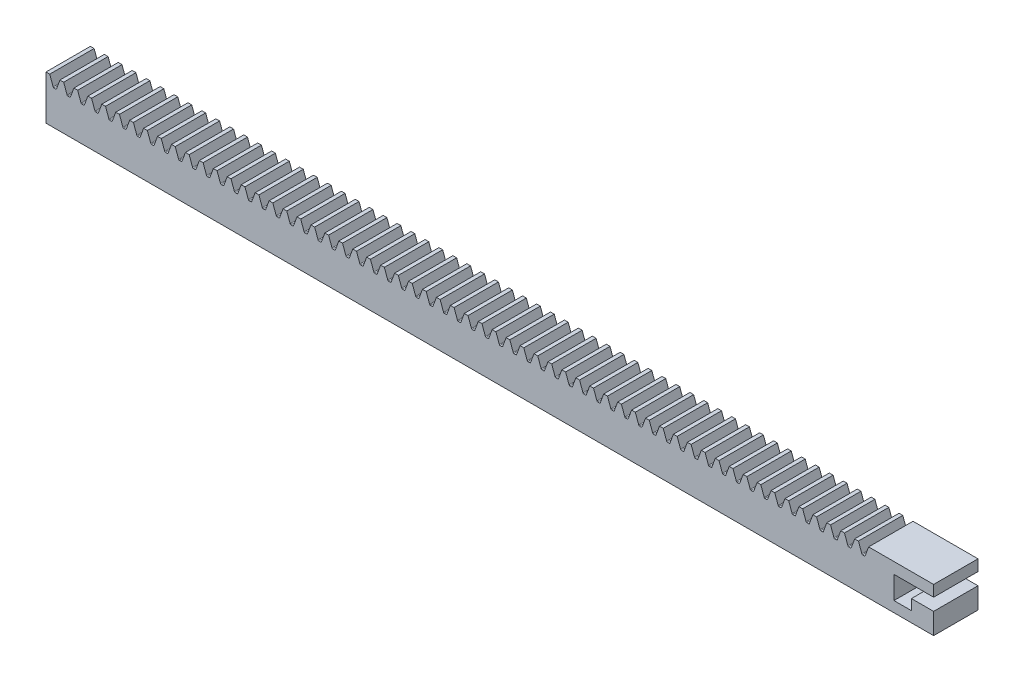
SolidWorks part; units mm, degrees
ref_plane "Front" through (0, 0, 0) normal (0, 0, 1) x (1, 0, 0)
ref_plane "Top" through (0, 0, 0) normal (0, 1, 0) x (1, 0, 0)
ref_plane "Right" through (0, 0, 0) normal (1, 0, 0) x (0, 0, -1)
sketch "Sketch1" plane through (0, 0, 0) normal (0, 0, 1) x (1, 0, 0)
  line L0 (-127, 0) -> (381, 0) construction
  line L1 (-127, -6.35) -> (127, -6.35)
  line L2 (-127, -6.35) -> (-127, 6.35)
  line L3 (-127, 6.35) -> (127, 6.35)
  line L4 (127, -6.35) -> (127, 6.35)
  line L5 (-127, -6.35) -> (127, 6.35) construction
  line L6 (-127, 6.35) -> (127, -6.35) construction
  point P0 (0, 0)
extrude "Boss-Extrude1" add sketch "Sketch1" along normal mid plane 12.7
sketch "Sketch2" plane through (0, 0, 6.35) normal (0, 0, 1) x (1, 0, 0)
  line L0 (-125.9296, 6.35) -> (-124.8941, 3.5052)
  line L1 (127, 6.35) -> (-127, 6.35) construction
  line L2 (-124.8941, 3.5052) -> (-124.0456, 3.5052)
  line L3 (-124.0456, 3.5052) -> (-123.0102, 6.35)
  line L4 (-125.9296, 6.35) -> (-123.0102, 6.35)
  line L5 (-125.4673, 5.08) -> (-121.4775, 5.08) construction
  line L6 (-123.0102, 6.35) -> (-121.9397, 6.35) construction
  line L7 (-123.4724, 3.5052) -> (-123.4724, 6.35) construction
  line L8 (-124.4699, 6.35) -> (-124.4699, 3.5052) construction
  line L10 (-121.9397, 6.35) -> (-120.9043, 3.5052) construction
  line L11 (-121.4775, 6.35) -> (-121.4775, 3.5052) construction
  line L12 (-125.9296, 6.35) -> (-127, 6.35) construction
  point P7 (-123.4724, 5.08)
  point P14 (-125.4673, 5.08)
  dimension "D1" = 1.27
  dimension "D3" = 3.9898
  dimension "D4" = 2.8448
  dimension "D6" = 1.9949
  dimension "D2" = 20
  dimension "D7" = 20
  dimension "D5" = 1.0704
  dimension "D9" = 0.8486
extrude "Cut-Extrude1" cut sketch "Sketch2" against normal blind 12.7
fillet "Fillet3" radius 0.2546 2 edges at (-124.0456, 3.5052, 0) (-124.8941, 3.5052, 0)
pattern_linear "LPattern4" count 59 spacing 3.9898 along (1, 0, 0) of "Cut-Extrude1", "Fillet3"
sketch "Ref" plane through (0, 0, 6.35) normal (0, 0, 1) x (1, 0, 0)
  line L0 (-127, 5.08) -> (127, 5.08) construction
  line L1 (-127, -6.35) -> (-127, 6.35) construction
  line L2 (127, -6.35) -> (127, 6.35) construction
  line L3 (-125.4673, 5.08) -> (-121.4775, 5.08) construction
sketch "Sketch3" plane through (0, 0, 6.35) normal (0, 0, 1) x (1, 0, 0)
  line L1 (127, 6.35) -> (108.4001, 6.35) construction
  line L9 (127, 3.175) -> (115.65, 3.175)
  line L10 (127, -6.35) -> (127, 6.35) construction
  line L11 (115.65, 3.175) -> (115.65, -3.325)
  line L12 (115.65, -3.325) -> (120.65, -3.325)
  line L13 (120.65, -3.325) -> (120.65, -0.325)
  line L14 (120.65, -0.325) -> (127, -0.325)
  line L15 (127, 3.175) -> (127, -0.325)
  dimension "D1" = 5
  dimension "D2" = 3
  dimension "D3" = 3.5
  dimension "D4" = 3.175
  dimension "D5" = 6.35
extrude "Cut-Extrude2" cut sketch "Sketch3" against normal through all
equation "\"D1@Sketch2\" = 1/\"Diamteral Pitch@Sketch1\""
equation "\"D3@Sketch2\" = 3.1416/\"Diamteral Pitch@Sketch1\""
equation "\"D4@Sketch2\" = (2.2/\"Diamteral Pitch@Sketch1\")+.002"
equation "\"D3@LPattern4\" =\"D3@Sketch2\""
equation "\"D1@Fillet3\" = \"D9@Sketch2\"*.3"
equation "\"D1@Cut-Extrude1\" = \"D1@Boss-Extrude1\""
